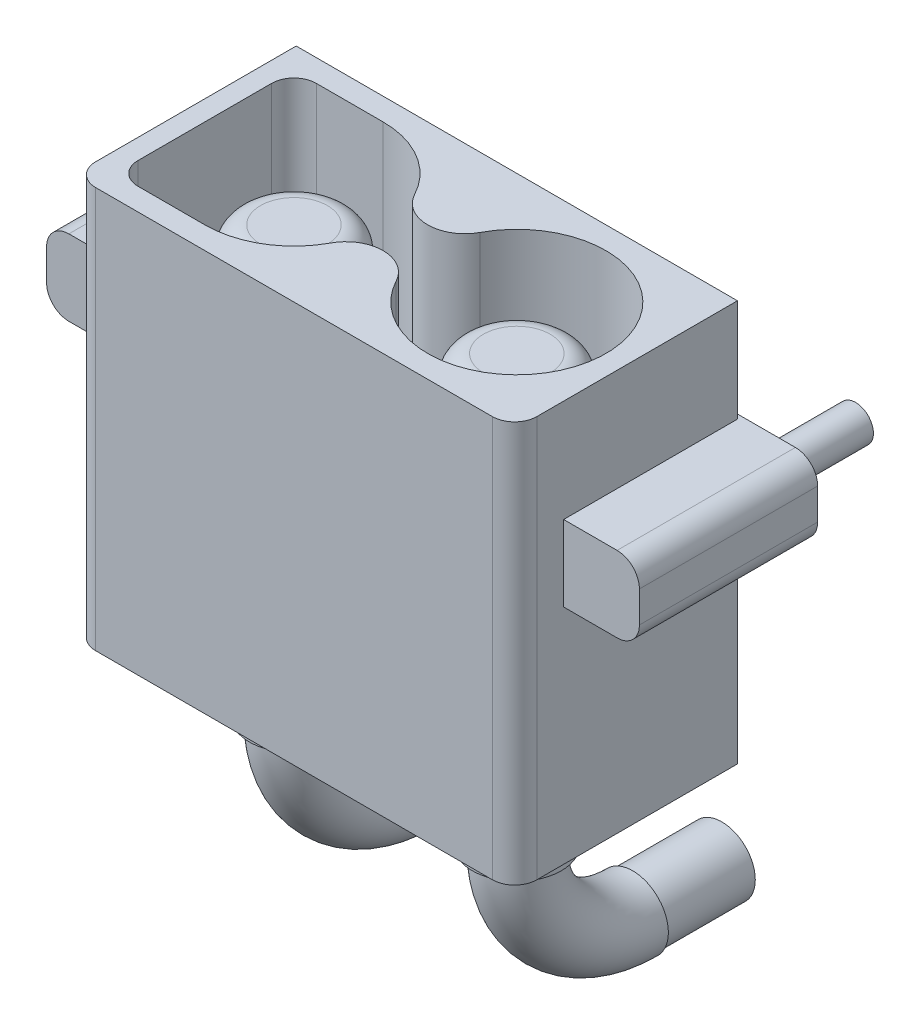
SolidWorks part; units mm, degrees
material "5052-H38"
ref_plane "Front" through (0, 0, 0) normal (0, 0, 1) x (1, 0, 0)
ref_plane "Top" through (0, 0, 0) normal (0, 1, 0) x (1, 0, 0)
ref_plane "Right" through (0, 0, 0) normal (1, 0, 0) x (0, 0, -1)
sketch "ｽｹｯﾁ1" plane through (0, 0, 0) normal (0, 0, 1) x (1, 0, 0)
  circle A0 centre (0, 0) radius 0.75
  point P2 (0, 0)
  dimension "D1" = 1.5
extrude "ﾎﾞｽ - 押し出し1" add sketch "ｽｹｯﾁ1" against normal blind 2
sketch "ｽｹｯﾁ2" plane through (0, 0, 0) normal (0, 0, 1) x (1, 0, 0)
  circle A0 centre (0, 0) radius 0.8
  dimension "D1" = 1.6
sketch "ｽｹｯﾁ3" plane through (0, 0, 0) normal (1, 0, 0) x (0, 0, -1)
  line L0 (-2.6, 2.6) -> (0, 2.6) construction
  line L1 (0, 2.6) -> (0, 0) construction
  arc A0 (0, 0) -> (-2.6, 2.6) centre (0, 2.6) cw
  dimension "D1" = 2.6
sweep "ｽｲｰﾌﾟ1" add profiles "ｽｹｯﾁ2" path "ｽｹｯﾁ3"
sketch "ｽｹｯﾁ4" plane through (0, 2.6, 0) normal (0, 1, 0) x (1, 0, 0)
  circle A0 centre (0, -2.6) radius 1
  circle A1 centre (0, -2.6) radius 0.8 construction
  point P2 (0, -2.6)
  dimension "D1" = 2
extrude "ﾎﾞｽ - 押し出し2" add sketch "ｽｹｯﾁ4" along normal blind 1.55
sketch "ｽｹｯﾁ5" plane through (0, 4.15, 0) normal (0, 1, 0) x (1, 0, 0)
  line L0 (2.45, -0.1) -> (2.45, -5.1)
  line L1 (2.45, -5.1) -> (-7.45, -5.1)
  line L2 (-7.45, -5.1) -> (-7.45, -0.1)
  line L3 (-7.45, -0.1) -> (2.45, -0.1)
  line L4 (0, -2.6) -> (2.45, -2.6) construction
  line L5 (0, -2.6) -> (-2.5, -2.6) construction
  line L6 (-2.5, -2.6) -> (-2.5, -0.1) construction
  dimension "D1" = 5
  dimension "D2" = 9.9
  dimension "D3" = 2.5
extrude "ﾎﾞｽ - 押し出し3" add sketch "ｽｹｯﾁ5" along normal blind 9
sketch "ｽｹｯﾁ8" plane through (0, 0, 0) normal (0, 0, 1) x (1, 0, 0)
  line L0 (0, 0) -> (0, 10) construction
  line L1 (0, 10) -> (-8, 10) construction
  line L2 (0, 10) -> (3, 10) construction
  circle A0 centre (-8, 10) radius 0.4
  circle A1 centre (3, 10) radius 0.4
  dimension "D4" = 0.8
  dimension "D1" = 10
  dimension "D2" = 8
  dimension "D3" = 3
extrude "ﾎﾞｽ - 押し出し5" add sketch "ｽｹｯﾁ8" against normal blind 2 separate body
sketch "ｽｹｯﾁ9" plane through (0, 0, 0) normal (0, 0, 1) x (1, 0, 0)
  line L0 (-9.15, 10.85) -> (-9.15, 9.15)
  line L1 (-9.15, 9.15) -> (-6.45, 9.15)
  line L2 (-6.45, 9.15) -> (-6.45, 10.85)
  line L3 (-6.45, 10.85) -> (-9.15, 10.85)
  line L4 (-8, 10) -> (-9.15, 10) construction
  line L6 (2.45, 13.15) -> (2.45, 4.15) construction
  line L7 (1.45, 10.85) -> (1.45, 9.15)
  line L8 (1.45, 9.15) -> (4.15, 9.15)
  line L9 (4.15, 9.15) -> (4.15, 10.85)
  line L10 (4.15, 10.85) -> (1.45, 10.85)
  line L11 (3, 10) -> (4.15, 10) construction
  dimension "D1" = 4.15
  dimension "D2" = 1
  dimension "D3" = 1.7
extrude "ﾎﾞｽ - 押し出し6" add sketch "ｽｹｯﾁ9" along normal blind 4
sketch "ｽｹｯﾁ6" plane through (0, 13.15, 0) normal (0, 1, 0) x (1, 0, 0)
  line L0 (0, -0.6) -> (-7, -0.6)
  line L2 (-7, -0.6) -> (-7, -4.6)
  line L7 (-7, -4.6) -> (0, -4.6)
  line L8 (0, 0) -> (0, -2.6) construction
  line L9 (0, -2.6) -> (2.45, -2.6) construction
  line L10 (2.45, -5.1) -> (2.45, -0.1) construction
  arc A1 (0, -0.6) -> (0, -4.6) centre (0, -2.6) cw
  dimension "D1" = 4
  dimension "D2" = 7
extrude "ｶｯﾄ - 押し出し3" cut sketch "ｽｹｯﾁ6" against normal blind 7
sketch "ｽｹｯﾁ7" plane through (0, 6.15, 0) normal (0, 1, 0) x (1, 0, 0)
  circle A0 centre (0, -2.6) radius 1.25
  arc A2 (0, -4.6) -> (0, -0.6) centre (0, -2.6) ccw construction
  dimension "D1" = 2.5
extrude "ﾎﾞｽ - 押し出し7" add sketch "ｽｹｯﾁ7" along normal blind 6
pattern_linear "直線ﾊﾟﾀｰﾝ1" count 2 spacing 5 along (-1, 0, 0) of "ﾎﾞｽ - 押し出し1", "ｽｲｰﾌﾟ1", "ﾎﾞｽ - 押し出し2", "ﾎﾞｽ - 押し出し7"
ref_plane "平面1" through (0, 0, 2.6) normal (0, 0, -1) x (-1, 0, 0)
sketch "ｽｹｯﾁ10" plane through (0, 13.15, 0) normal (0, 1, 0) x (1, 0, 0)
  line L1 (0, -0.6) -> (-7, -0.6) construction
  line L2 (-3.2353, -1.6588) -> (-1.7647, -1.6588) construction
  line L5 (-5, -0.6) -> (0, -0.6)
  line L6 (-2.5, -2.1) -> (-2.5, -0.6) construction
  arc A3 (0, -0.6) -> (-1.7647, -1.6588) centre (0, -2.6) ccw
  arc A4 (-5, -0.6) -> (-3.2353, -1.6588) centre (-5, -2.6) cw
  arc A5 (-3.2353, -1.6588) -> (-1.7647, -1.6588) centre (-2.5, -1.2667) ccw
  dimension "D1" = 1.5
extrude "ﾎﾞｽ - 押し出し8" add sketch "ｽｹｯﾁ10" against normal up to surface (7 mm away) up to face at (-5, 6.15, 1.35)
mirror "ﾐﾗｰ2" about plane through (0, 0, 2.6) normal (0, 0, -1) of "ﾎﾞｽ - 押し出し8"
fillet "ﾌｨﾚｯﾄ1" radius 0.5 4 edges at (-9.15, 10.85, 2) (-9.15, 9.15, 2) (4.15, 10.85, 2) (4.15, 9.15, 2)
fillet "ﾌｨﾚｯﾄ2" radius 0.5 2 edges at (2.45, 8.65, 5.1) (-7.45, 8.65, 5.1)
fillet "ﾌｨﾚｯﾄ4" radius 0.5 2 edges at (-7, 9.65, 4.6) (-7, 9.65, 0.6)
fillet "ﾌｨﾚｯﾄ5" radius 0.5 2 edges at (0, 12.15, 3.85) (-5, 12.15, 3.85)
